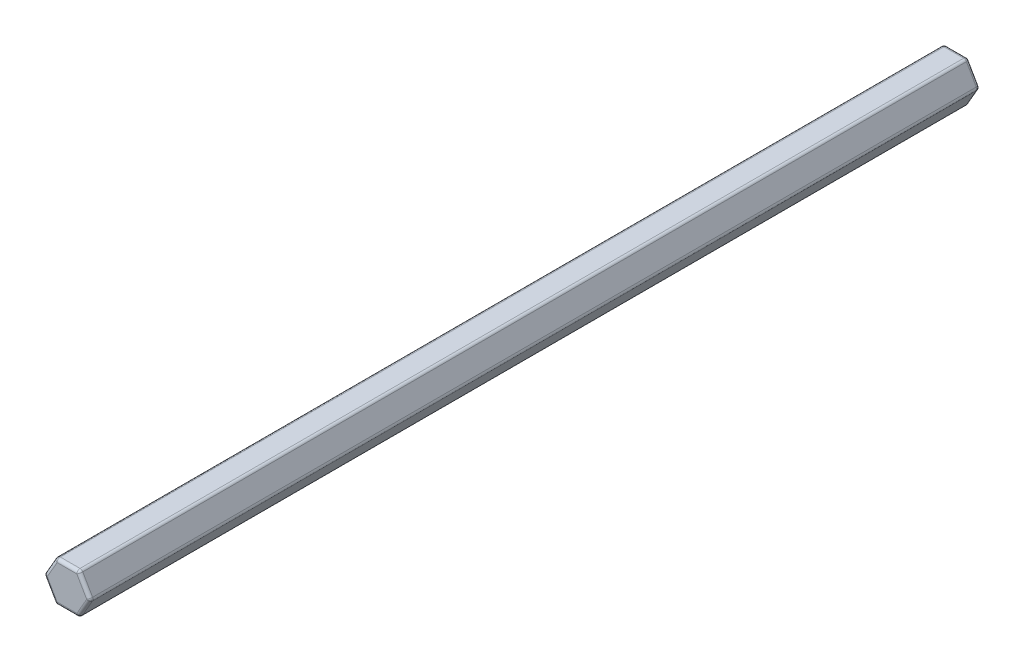
SolidWorks part; units mm, degrees
ref_plane "Front Plane" through (0, 0, 0) normal (0, 0, 1) x (1, 0, 0)
ref_plane "Top Plane" through (0, 0, 0) normal (0, 1, 0) x (1, 0, 0)
ref_plane "Right Plane" through (0, 0, 0) normal (1, 0, 0) x (0, 0, -1)
sketch "Sketch1" plane through (0, 0, 0) normal (0, 0, 1) x (1, 0, 0)
  line L1 (7.3323, 0) -> (3.6662, 6.35)
  line L2 (3.6662, 6.35) -> (-3.6662, 6.35)
  line L3 (-3.6662, 6.35) -> (-7.3323, 0)
  line L4 (-7.3323, 0) -> (-3.6662, -6.35)
  line L5 (-3.6662, -6.35) -> (3.6662, -6.35)
  line L6 (3.6662, -6.35) -> (7.3323, 0)
  circle A0 centre (0, 0) radius 6.35 construction
  point P1 (7.1859, -1.458)
  point P10 (0, 0)
  dimension "D1" = 12.7
extrude "Boss-Extrude1" add sketch "Sketch1" along normal mid plane 279.4
fillet "Fillet1" radius 1 18 edges at (3.6662, -6.35, 0) (-3.6662, -6.35, 0) (-7.3323, 0, 0) (-3.6662, 6.35, 0) (7.3323, 0, 0) (3.6662, 6.35, 0) (5.4993, 3.175, -139.7) (0, 6.35, -139.7) (-5.4993, 3.175, -139.7) (-5.4993, -3.175, -139.7) (0, -6.35, -139.7) (5.4993, -3.175, -139.7) (0, -6.35, 139.7) (-5.4993, -3.175, 139.7) (-5.4993, 3.175, 139.7) (0, 6.35, 139.7) (5.4993, 3.175, 139.7) (5.4993, -3.175, 139.7)
